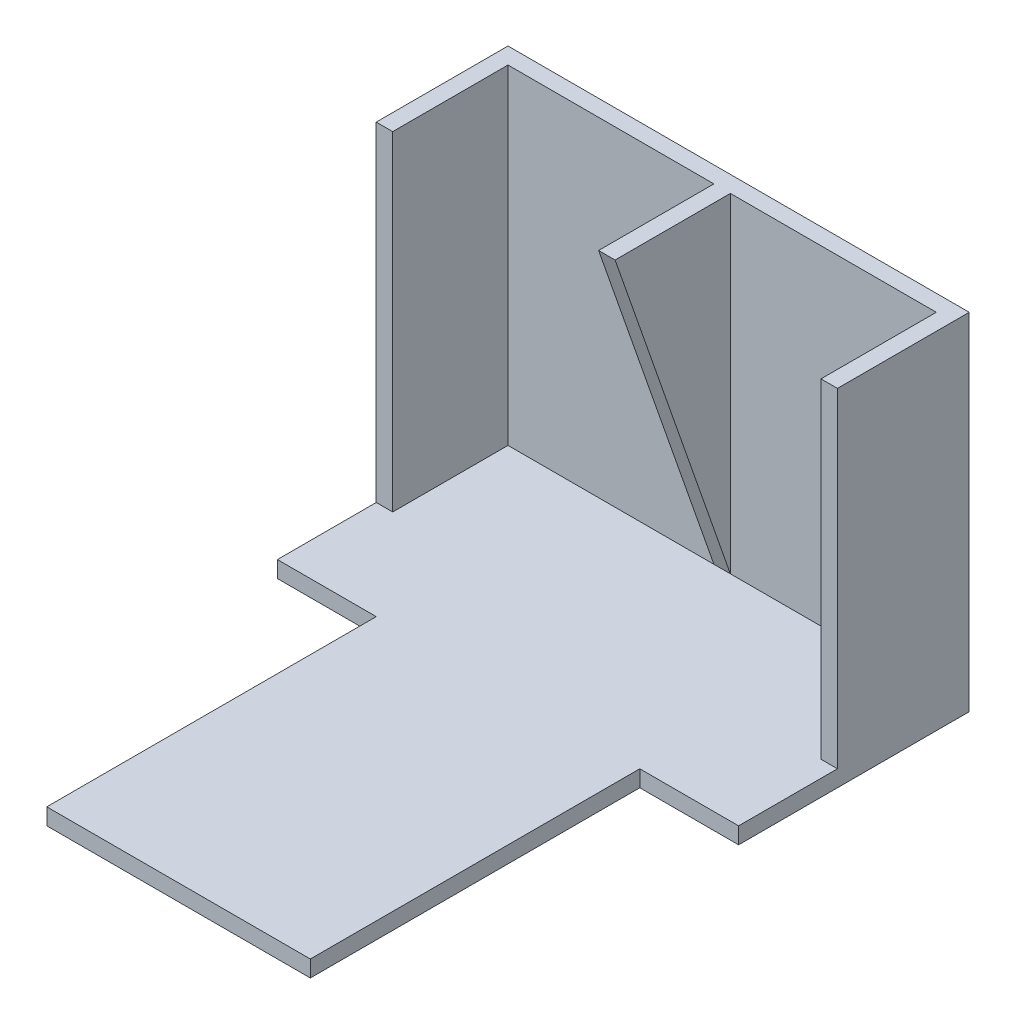
SolidWorks part; units mm, degrees
material "PBT General Purpose"
ref_plane "Front Plane" through (0, 0, 0) normal (0, 0, 1) x (1, 0, 0)
ref_plane "Top Plane" through (0, 0, 0) normal (0, 1, 0) x (1, 0, 0)
ref_plane "Right Plane" through (0, 0, 0) normal (1, 0, 0) x (0, 0, -1)
sketch "Sketch1" plane through (0, 0, 0) normal (0, 1, 0) x (1, 0, 0)
  line L0 (20, -17.5) -> (35, -17.5)
  line L1 (-35, -17.5) -> (-20, -17.5)
  line L2 (-35, -17.5) -> (-35, 17.5)
  line L3 (-35, 17.5) -> (35, 17.5)
  line L4 (35, -17.5) -> (35, 17.5)
  line L5 (-35, -17.5) -> (35, 17.5) construction
  line L6 (-35, 17.5) -> (35, -17.5) construction
  line L8 (20, -17.5) -> (20, -67.5)
  line L9 (20, -67.5) -> (-20, -67.5)
  line L10 (-20, -17.5) -> (-20, -67.5)
  point P0 (0, 0)
  dimension "D1" = 70
  dimension "D2" = 35
  dimension "D3" = 50
  dimension "D4" = 40
extrude "Boss-Extrude1" add sketch "Sketch1" along normal blind 2.5
sketch "Sketch3" plane through (0, 2.5, 0) normal (0, 1, 0) x (1, 0, 0)
  line L0 (0, 15) -> (0, 17.5) construction
  line L1 (-35, 17.5) -> (-32.5, 17.5)
  line L2 (-35, 17.5) -> (-35, -2.5)
  line L3 (-35, -2.5) -> (-32.5, -2.5)
  line L4 (-32.5, 15) -> (-32.5, -2.5)
  line L5 (35, 17.5) -> (32.5, 17.5)
  line L6 (35, 17.5) -> (35, -2.5)
  line L7 (35, -2.5) -> (32.5, -2.5)
  line L8 (32.5, 15) -> (32.5, -2.5)
  line L9 (32.5, 17.5) -> (-32.5, 17.5)
  line L11 (32.5, 15) -> (1.25, 15)
  line L13 (-1.25, 15) -> (-32.5, 15)
  line L14 (-1.25, -2.5) -> (1.25, -2.5)
  line L15 (-1.25, -2.5) -> (-1.25, 15)
  line L17 (1.25, -2.5) -> (1.25, 15)
  line L18 (1.25, 15) -> (-1.25, 15) construction
  point P18 (0, 15)
  dimension "D1" = 2.5
  dimension "D2" = 20
extrude "Boss-Extrude2" add sketch "Sketch3" along normal blind 50
sketch "Sketch4" plane through (1.25, 0, 0) normal (1, 0, 0) x (0, 0, -1)
  line L0 (15, 2.5) -> (-2.5, 52.5)
  line L1 (-2.5, 52.5) -> (-2.5, 2.5)
  line L2 (-2.5, 2.5) -> (15, 2.5)
extrude "Cut-Extrude1" cut sketch "Sketch4" against normal up to next
